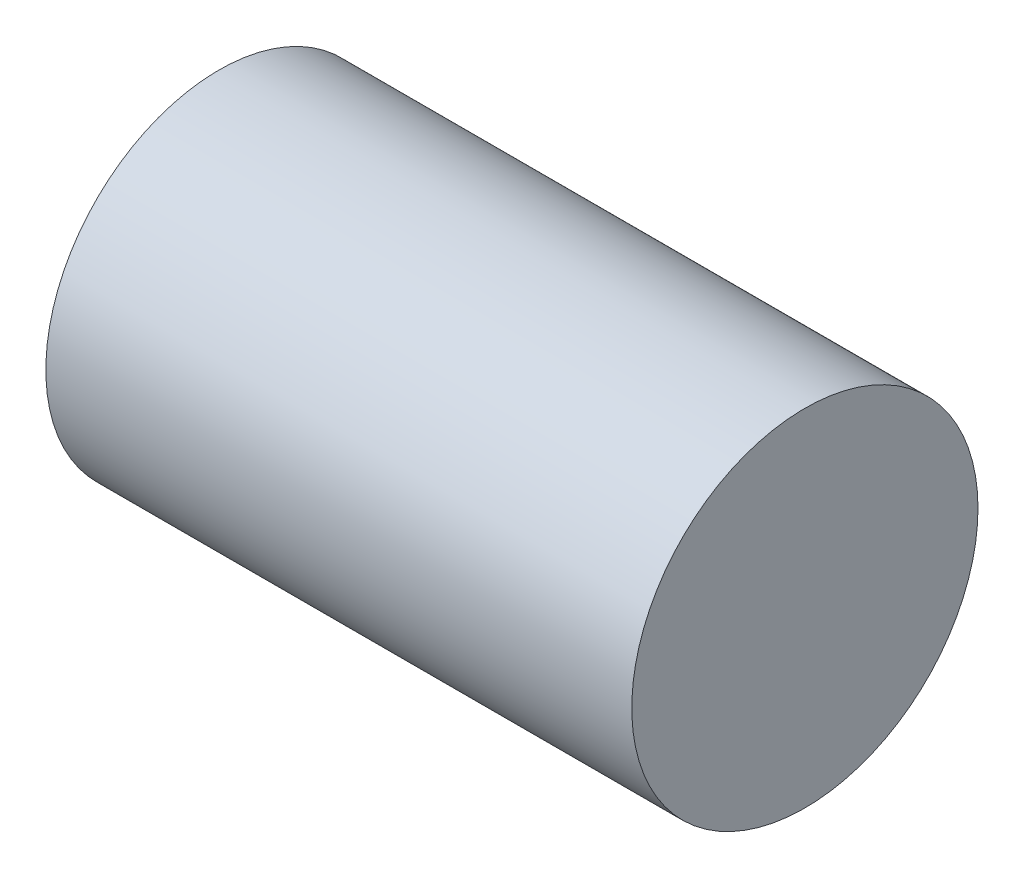
SolidWorks part; units mm, degrees
ref_plane "Front Plane" through (0, 0, 0) normal (1, 0, 0) x (0, 1, 0)
ref_plane "Top Plane" through (0, 0, 0) normal (0, 0, 1) x (0, 1, 0)
ref_plane "Right Plane" through (0, 0, 0) normal (0, 1, 0) x (-1, 0, 0)
sketch "Sketch1" plane through (0, 0, 0) normal (1, 0, 0) x (0, 1, 0)
  circle A0 centre (0, 0) radius 6.5
  dimension "D1" = 13
extrude "Boss-Extrude1" add sketch "Sketch1" along normal blind 22 contours A0
